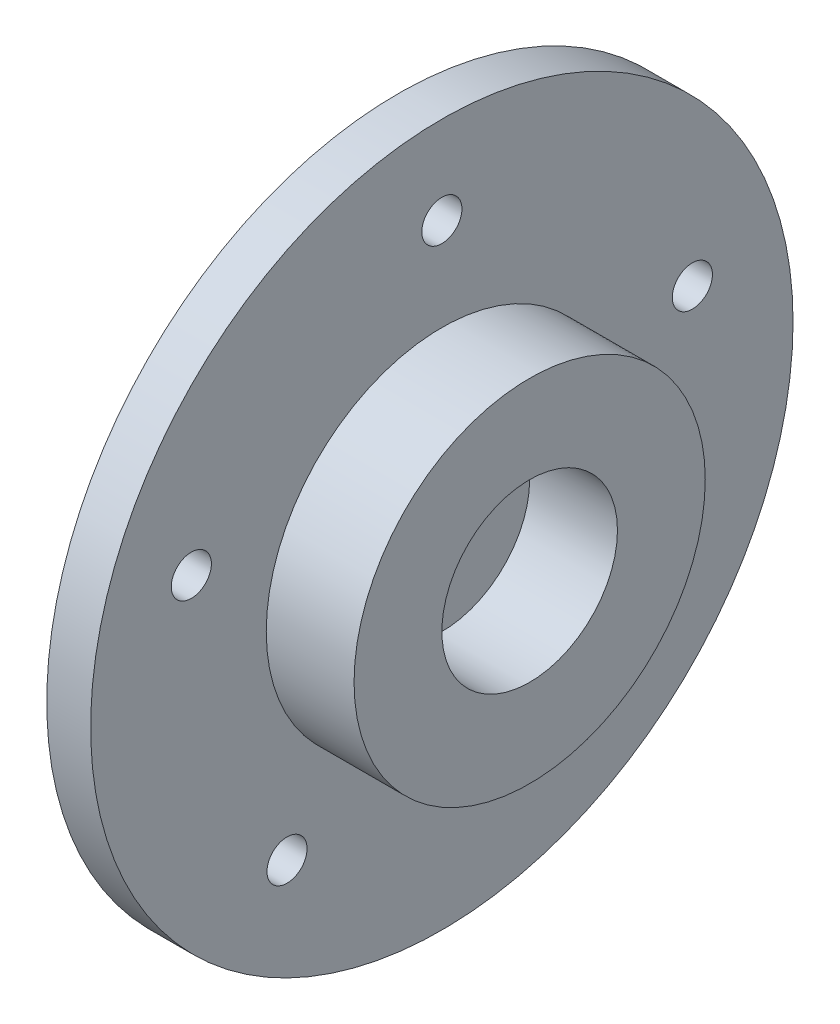
SolidWorks part; units mm, degrees
ref_plane "Front Plane" through (0, 0, 0) normal (0, 0, 1) x (1, 0, 0)
ref_plane "Top Plane" through (0, 0, 0) normal (0, 1, 0) x (1, 0, 0)
ref_plane "Right Plane" through (0, 0, 0) normal (1, 0, 0) x (0, 0, -1)
sketch "Sketch1" plane through (0, 0, 0) normal (1, 0, 0) x (0, 0, -1)
  line L0 (-36.2353, 12.4848) -> (0, 0.7113) construction
  line L1 (0, 0.7113) -> (36.2353, 12.4848) construction
  line L2 (0, 38.8113) -> (0, 0.7113) construction
  line L3 (0, 0.7113) -> (22.3946, -30.1122) construction
  line L4 (-22.3946, -30.1122) -> (0, 0.7113) construction
  circle A0 centre (0, 0.7113) radius 25.4 construction
  circle A1 centre (-36.2353, 12.4848) radius 2.9
  circle A2 centre (-22.3946, -30.1122) radius 2.9
  circle A3 centre (22.3946, -30.1122) radius 2.9
  circle A4 centre (36.2353, 12.4848) radius 2.9
  circle A5 centre (0, 38.8113) radius 2.9
  circle A6 centre (0, 0.7113) radius 50.8
  circle A7 centre (0, 0.7113) radius 38.1 construction
  point P13 (0, 0)
  point P15 (0, 0.7113)
  dimension "D2" = 5.8
  dimension "D3" = 50.8
  dimension "D4" = 101.6
  dimension "D1" = 38.1
  dimension "D5" = 72
  dimension "D6" = 72
  dimension "D7" = 72
  dimension "D8" = 72
  dimension "D9" = 72
extrude "Boss-Extrude1" add sketch "Sketch1" along normal blind 6.35
sketch "Sketch2" plane through (6.35, 0, 0) normal (1, 0, 0) x (0, 0, -1)
  circle A0 centre (0, 0) radius 25.4
  dimension "D1" = 50.8
extrude "Boss-Extrude2" add sketch "Sketch2" along normal blind 12.7
sketch "Sketch3" plane through (19.05, 0, 0) normal (1, 0, 0) x (0, 0, -1)
  circle A0 centre (0, 0) radius 12.7
  dimension "D1" = 25.4
extrude "Cut-Extrude1" cut sketch "Sketch3" against normal blind 12.7
